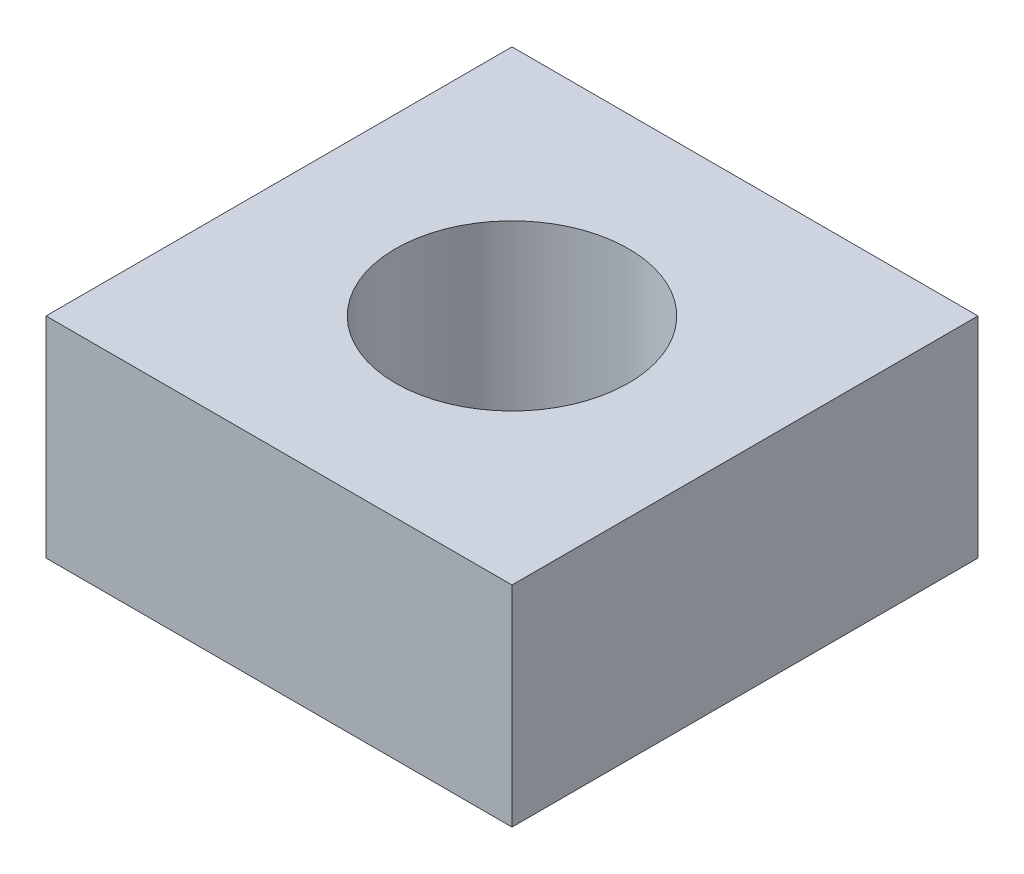
SolidWorks part; units mm, degrees
ref_plane "Front Plane" through (0, 0, 0) normal (0, 0, 1) x (1, 0, 0)
ref_plane "Top Plane" through (0, 0, 0) normal (0, 1, 0) x (1, 0, 0)
ref_plane "Right Plane" through (0, 0, 0) normal (1, 0, 0) x (0, 0, -1)
sketch "Sketch1" plane through (0, 0, 0) normal (0, 1, 0) x (1, 0, 0)
  line L1 (5, -5) -> (-5, -5)
  line L2 (5, -5) -> (5, 5)
  line L3 (5, 5) -> (-5, 5)
  line L4 (-5, -5) -> (-5, 5)
  line L5 (5, -5) -> (-5, 5) construction
  line L6 (5, 5) -> (-5, -5) construction
  circle A0 centre (0, 0) radius 2.5
  point P0 (0, 0)
  dimension "D1" = 10
  dimension "D2" = 10
extrude "Boss-Extrude1" add sketch "Sketch1" along normal blind 4.5
